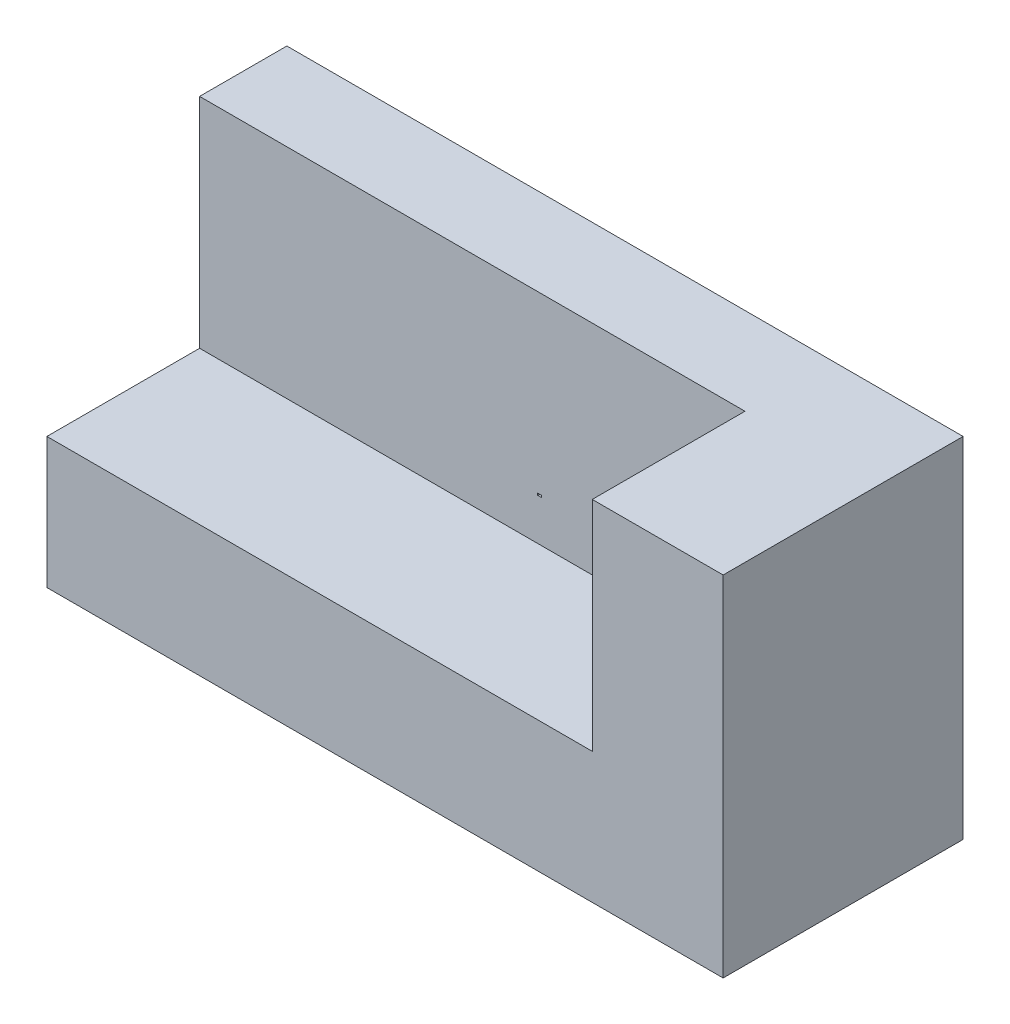
SolidWorks part; units mm, degrees
ref_plane "Plano frontal" through (0, 0, 0) normal (0, 0, 1) x (1, 0, 0)
ref_plane "Plano superior" through (0, 0, 0) normal (0, 1, 0) x (1, 0, 0)
ref_plane "Plano direito" through (0, 0, 0) normal (1, 0, 0) x (0, 0, -1)
sketch "Esboço1" plane through (0, 0, 0) normal (0, 0, 1) x (1, 0, 0)
  line L1 (-31, -16) -> (31, -16)
  line L2 (-31, -16) -> (-31, 16)
  line L3 (-31, 16) -> (31, 16)
  line L4 (31, -16) -> (31, 16)
  line L5 (-31, -16) -> (31, 16) construction
  line L6 (-31, 16) -> (31, -16) construction
  line L7 (0.3463, -0.1787) -> (0, -0.1787)
  line L8 (0.3463, -0.1787) -> (0.3463, 0)
  line L9 (0.3463, 0) -> (0, 0)
  line L10 (0, -0.1787) -> (0, 0)
  line L11 (0.3463, -0.1787) -> (0, 0) construction
  line L12 (0.3463, 0) -> (0, -0.1787) construction
  point P0 (0, 0)
  point P6 (0.1731, -0.0894)
  dimension "D1" = 62
  dimension "D2" = 32
extrude "Ressalto-extrusão1" add sketch "Esboço1" along normal blind 22
sketch "Esboço2" plane through (0, 0, 22) normal (0, 0, 1) x (1, 0, 0)
  line L0 (-31, 16) -> (-31, -4)
  line L1 (-31, 16) -> (-31, -16) construction
  line L2 (-31, -4) -> (19, -4)
  line L3 (19, 16) -> (19, -4)
  line L4 (31, 16) -> (-31, 16) construction
  line L6 (-31, 16) -> (19, 16)
  dimension "D1" = 12
  dimension "D2" = 12
extrude "Corte-extrusão4" cut sketch "Esboço2" against normal blind 14 and the other way through all
